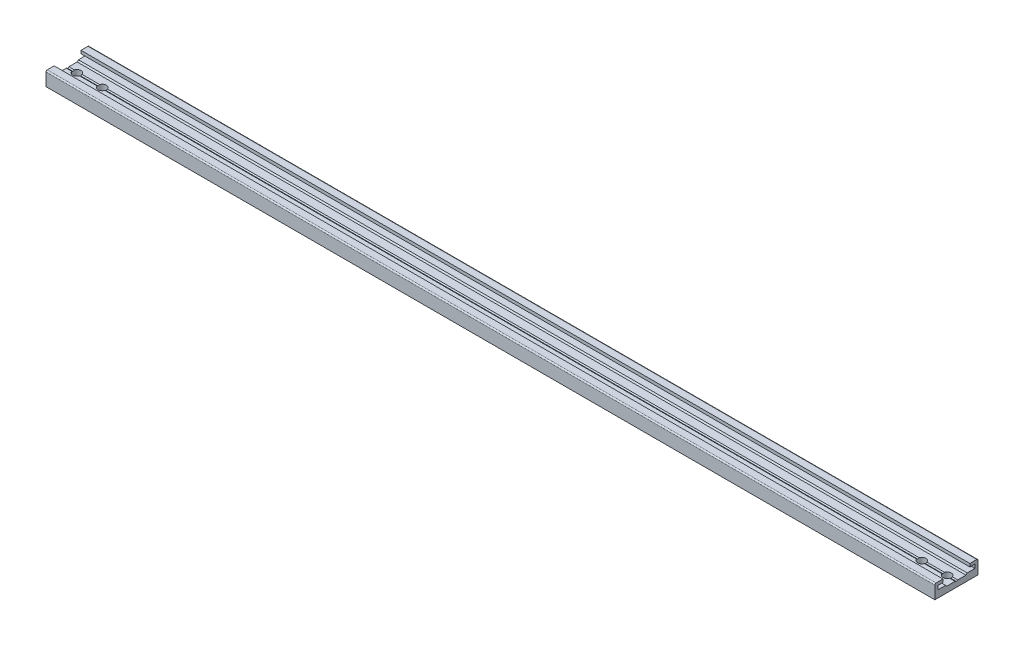
SolidWorks part; units mm, degrees
material "6061 Alloy"
ref_plane "Front" through (0, 0, 0) normal (0, 0, 1) x (1, 0, 0)
ref_plane "Top" through (0, 0, 0) normal (0, 1, 0) x (1, 0, 0)
ref_plane "Right" through (0, 0, 0) normal (1, 0, 0) x (0, 0, -1)
sketch "Sketch1" plane through (0, 0, 0) normal (1, 0, 0) x (0, 0, -1)
  line L0 (0, -2.75) -> (0, 2.75) construction
  line L1 (-0.5, -0.45) -> (0, -0.7387) construction
  line L2 (-3.75, -0.45) -> (-0.5, -0.45) construction
  line L3 (-4.25, 0.05) -> (-3.75, -0.45) construction
  line L4 (-7.3, 0.05) -> (-4.25, 0.05) construction
  line L5 (-7.3, 1.55) -> (-7.3, 0.05) construction
  line L6 (-5.3, 1.55) -> (-7.3, 1.55) construction
  line L7 (-5.3, 2.75) -> (-5.3, 1.55) construction
  line L8 (-8, 2.75) -> (-5.3, 2.75) construction
  line L9 (-8.5, -2.75) -> (-8.5, 2.25) construction
  line L39 (-8.5, -2.75) -> (8.5, -2.75) construction
  line L40 (8.5, -2.75) -> (8.5, 2.25) construction
  line L41 (8, 2.75) -> (5.3, 2.75) construction
  line L42 (5.3, 2.75) -> (5.3, 1.55) construction
  line L43 (5.3, 1.55) -> (7.3, 1.55) construction
  line L44 (7.3, 1.55) -> (7.3, 0.05) construction
  line L45 (7.3, 0.05) -> (4.25, 0.05) construction
  line L46 (4.25, 0.05) -> (3.75, -0.45) construction
  line L47 (3.75, -0.45) -> (0.5, -0.45) construction
  line L48 (0.5, -0.45) -> (0, -0.7387) construction
  arc A0 (8, 2.75) -> (8.5, 2.25) centre (8, 2.25) cw construction
  arc A1 (-8, 2.75) -> (-8.5, 2.25) centre (-8, 2.25) ccw construction
  point P1 (7.3, 0.8)
  point P26 (0, 0)
  point P32 (0, -1.75)
  dimension "D12" = 0.5
  dimension "D1" = 30
  dimension "D3" = 2.3
  dimension "Rail Height" = 5.5
  dimension "D4" = 2.0113
  dimension "D5" = 2.8
  dimension "D7" = 1.2
  dimension "D8" = 3.2
  dimension "D9" = 1.2
  dimension "D10" = 45
  dimension "D11" = 3.75
  dimension "Rail Width" = 17
  dimension "Mounting Hole Depth" = 1
sketch "Sketch2" plane through (0, 0, 0) normal (0, 0, 1) x (1, 0, 0)
  line L0 (1000, 0) -> (-1000, 0) construction
  point P0 (-960, 0)
  point P3 (-900, 0)
  point P4 (0, 0)
  point P6 (-884, 0)
  point P7 (988, 0)
  dimension "Rail Length" = 2000
  dimension "Mounting Hole Ctr to End" = 40
  dimension "Mounting Hole Ctr to Ctr" = 60
  dimension "D2" = 12
  dimension "D1" = 16
sketch "Sketch5" plane through (0, 0, 0) normal (1, 0, 0) x (0, 0, -1)
  line L0 (-8.5, -2.75) -> (8.5, -2.75) construction
  line L1 (8.5, -2.75) -> (8.5, 2.25) construction
  line L2 (8, 2.75) -> (5.3, 2.75) construction
  line L3 (5.3, 2.75) -> (5.3, 1.55) construction
  line L4 (5.3, 1.55) -> (7.3, 1.55) construction
  line L5 (7.3, 1.55) -> (7.3, 0.05) construction
  line L6 (7.3, 0.05) -> (4.25, 0.05) construction
  line L7 (4.25, 0.05) -> (3.75, -0.45) construction
  line L8 (3.75, -0.45) -> (0.5, -0.45) construction
  line L9 (0.5, -0.45) -> (0, -0.7387) construction
  line L10 (-0.5, -0.45) -> (0, -0.7387) construction
  line L11 (-3.75, -0.45) -> (-0.5, -0.45) construction
  line L12 (-4.25, 0.05) -> (-3.75, -0.45) construction
  line L13 (-7.3, 0.05) -> (-4.25, 0.05) construction
  line L14 (-7.3, 1.55) -> (-7.3, 0.05) construction
  line L15 (-5.3, 1.55) -> (-7.3, 1.55) construction
  line L16 (-5.3, 2.75) -> (-5.3, 1.55) construction
  line L17 (-8, 2.75) -> (-5.3, 2.75) construction
  line L18 (-8.5, -2.75) -> (-8.5, 2.25) construction
  line L19 (-8.5, -2.75) -> (8.5, -2.75)
  line L20 (8.5, -2.75) -> (8.5, 2.25)
  line L21 (8, 2.75) -> (5.3, 2.75)
  line L22 (5.3, 2.75) -> (5.3, 1.55)
  line L23 (5.3, 1.55) -> (7.3, 1.55)
  line L24 (7.3, 1.55) -> (7.3, 0.05)
  line L25 (7.3, 0.05) -> (4.25, 0.05)
  line L26 (4.25, 0.05) -> (3.75, -0.45)
  line L27 (3.75, -0.45) -> (0.5, -0.45)
  line L28 (0.5, -0.45) -> (0, -0.7387)
  line L29 (-0.5, -0.45) -> (0, -0.7387)
  line L30 (-3.75, -0.45) -> (-0.5, -0.45)
  line L31 (-4.25, 0.05) -> (-3.75, -0.45)
  line L32 (-7.3, 0.05) -> (-4.25, 0.05)
  line L33 (-7.3, 1.55) -> (-7.3, 0.05)
  line L34 (-5.3, 1.55) -> (-7.3, 1.55)
  line L35 (-5.3, 2.75) -> (-5.3, 1.55)
  line L36 (-8, 2.75) -> (-5.3, 2.75)
  line L37 (-8.5, -2.75) -> (-8.5, 2.25)
  arc A0 (8.5, 2.25) -> (8, 2.75) centre (8, 2.25) ccw construction
  arc A1 (-8, 2.75) -> (-8.5, 2.25) centre (-8, 2.25) ccw construction
  arc A2 (8.5, 2.25) -> (8, 2.75) centre (8, 2.25) ccw
  arc A3 (-8, 2.75) -> (-8.5, 2.25) centre (-8, 2.25) ccw
extrude "Boss-Extrude1" add sketch "Sketch5" along normal blind 350
sketch "Sketch3" plane through (0, 0, 0) normal (0, 0, 1) x (1, 0, 0)
  line L0 (-963.25, -0.45) -> (-963.25, -1.75)
  line L1 (-963.25, -1.75) -> (-961.75, -1.75)
  line L2 (-961.75, -1.75) -> (-961.75, -2.75)
  line L3 (-961.75, -2.75) -> (-960, -2.75)
  line L4 (-960, -2.75) -> (-960, -0.45)
  line L5 (-960, -0.45) -> (-963.25, -0.45)
  line L8 (-963.25, -0.45) -> (-956.75, -0.45) construction
  line L10 (-958.25, -2.75) -> (-961.75, -2.75) construction
  line L19 (350, -2.75) -> (0, -2.75) construction
  dimension "D1" = 1.3
  dimension "D2" = 6.5
  dimension "D3" = 3.5
revolve "Cut-Revolve1" [suppressed] cut sketch "Sketch3" angle 360 mid plane about L4
pattern_linear "LPattern1" [suppressed]
sketch "Sketch6" plane through (0, -0.45, 0) normal (0, 1, 0) x (1, 0, 0)
  circle A0 centre (13.6475, 0) radius 1.6 construction
  circle A1 centre (3.6475, 0) radius 1.6 construction
  circle A2 centre (346.3525, 0) radius 1.6 construction
  circle A3 centre (336.3525, 0) radius 1.6 construction
  circle A4 centre (13.6475, 0) radius 1.6
  circle A5 centre (3.6475, 0) radius 1.6
  circle A6 centre (346.3525, 0) radius 1.6
  circle A7 centre (336.3525, 0) radius 1.6
extrude "Cut-Extrude1" cut sketch "Sketch6" against normal through all
equation "\"D3@LPattern1\"=\"Mounting Hole Ctr to Ctr@Sketch2\""
equation "\"D2@Sketch2\"=\"Mounting Hole Ctr to End@Sketch2\"*.3"
equation "\"D1@Sketch2\"=\"Mounting Hole Ctr to End@Sketch2\"*.4"
